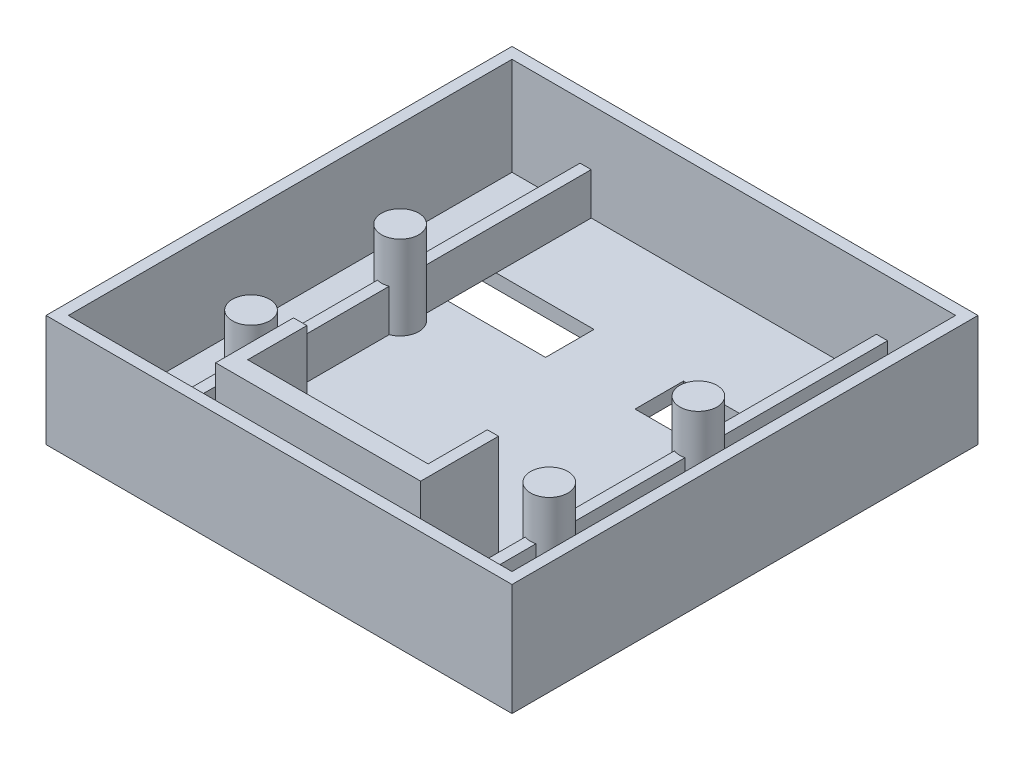
SolidWorks part; units mm, degrees
ref_plane "Alzado" through (0, 0, 0) normal (0, 0, 1) x (1, 0, 0)
ref_plane "Planta" through (0, 0, 0) normal (0, 1, 0) x (1, 0, 0)
ref_plane "Vista lateral" through (0, 0, 0) normal (1, 0, 0) x (0, 0, -1)
sketch "Croquis1" plane through (0, 0, 0) normal (0, 1, 0) x (1, 0, 0)
  line L1 (0, 0) -> (100, 0)
  line L2 (0, 0) -> (0, 100)
  line L3 (0, 100) -> (100, 100)
  line L4 (100, 0) -> (100, 100)
extrude "PlacaBase" add sketch "Croquis1" along normal blind 3
ref_plane "PL_SobreBase" through (0, 3, 0) normal (0, 1, 0) x (1, 0, 0)
sketch "Croquis2" plane through (0, 3, 0) normal (0, 1, 0) x (1, 0, 0)
  line L1 (0, 0) -> (100, 0)
  line L2 (0, 0) -> (0, 100)
  line L3 (0, 100) -> (100, 100)
  line L4 (100, 0) -> (100, 100)
  line L5 (2.4, 2.4) -> (97.6, 2.4)
  line L6 (2.4, 2.4) -> (2.4, 97.6)
  line L7 (2.4, 97.6) -> (97.6, 97.6)
  line L8 (97.6, 2.4) -> (97.6, 97.6)
extrude "Paredes" add sketch "Croquis2" along normal blind 21
sketch "RecortesRueda" plane through (0, 0, 0) normal (0, 1, 0) x (1, 0, 0)
  line L0 (0, 100) -> (0, 0) construction
  line L1 (0, 53) -> (14, 53)
  line L2 (0, 53) -> (0, 91)
  line L3 (0, 91) -> (14, 91)
  line L4 (14, 53) -> (14, 91)
  line L5 (100, 0) -> (100, 100) construction
  line L6 (86, 53) -> (100, 53)
  line L7 (86, 53) -> (86, 91)
  line L8 (86, 91) -> (100, 91)
  line L9 (100, 53) -> (100, 91)
ref_plane "PL_Motores" through (0, 7.3, 0) normal (0, 1, 0) x (1, 0, 0)
sketch "Croquis4" plane through (0, 7.3, 0) normal (0, 1, 0) x (1, 0, 0)
  line L0 (14, 53) -> (14, 91) construction
  line L1 (14, 66.8) -> (40.4, 66.8)
  line L2 (14, 66.8) -> (14, 77.2)
  line L3 (14, 77.2) -> (40.4, 77.2)
  line L4 (40.4, 66.8) -> (40.4, 77.2)
  line L5 (86, 53) -> (86, 91) construction
  line L6 (59.6, 66.8) -> (86, 66.8)
  line L7 (59.6, 66.8) -> (59.6, 77.2)
  line L8 (59.6, 77.2) -> (86, 77.2)
  line L9 (86, 66.8) -> (86, 77.2)
extrude "AlojamientosMotor" cut sketch "Croquis4" against normal blind 12.4
ref_plane "PL_Superior" through (0, 24, 0) normal (0, 1, 0) x (1, 0, 0)
sketch "BolsilloBateria" plane through (0, 24, 0) normal (0, 1, 0) x (1, 0, 0)
  line L1 (22, 26) -> (78, 26)
  line L2 (22, 26) -> (22, 57)
  line L3 (22, 57) -> (78, 57)
  line L4 (78, 26) -> (78, 57)
sketch "Croquis6" plane through (0, 3, 0) normal (0, 1, 0) x (1, 0, 0)
  line L0 (2.4, 2.4) -> (97.6, 2.4) construction
  line L1 (17, 2.4) -> (19.4, 2.4)
  line L2 (17, 2.4) -> (17, 97.6)
  line L3 (17, 97.6) -> (19.4, 97.6)
  line L4 (19.4, 2.4) -> (19.4, 97.6)
  line L5 (97.6, 97.6) -> (2.4, 97.6) construction
  line L7 (80.6, 2.4) -> (83, 2.4)
  line L8 (80.6, 2.4) -> (80.6, 97.6)
  line L9 (80.6, 97.6) -> (83, 97.6)
  line L10 (83, 2.4) -> (83, 97.6)
extrude "NerviosRigidez" add sketch "Croquis6" along normal blind 9
sketch "Croquis7" plane through (0, 3, 0) normal (0, 1, 0) x (1, 0, 0)
  line L0 (97.6, 2.4) -> (97.6, 97.6) construction
  line L1 (2.4, 2.4) -> (97.6, 2.4)
  line L2 (2.4, 2.4) -> (2.4, 8.4)
  line L3 (2.4, 8.4) -> (97.6, 8.4)
  line L4 (97.6, 2.4) -> (97.6, 8.4)
extrude "BloqueCuna" add sketch "Croquis7" along normal blind 10
sketch "Croquis8" plane through (0, 3, 0) normal (0, 1, 0) x (1, 0, 0)
  line L0 (80.6, 8.4) -> (19.4, 8.4) construction
  line L1 (28, 8.4) -> (72, 8.4)
  line L2 (28, 8.4) -> (28, 12.4)
  line L3 (28, 12.4) -> (72, 12.4)
  line L4 (72, 8.4) -> (72, 12.4)
extrude "TorreSensores" add sketch "Croquis8" along normal blind 22
sketch "VentanasSensoresLinea" plane through (0, 0, 0) normal (0, 1, 0) x (1, 0, 0)
  circle A0 centre (26, 24) radius 5
  circle A1 centre (74, 24) radius 5
  circle A2 centre (26, 94) radius 5
  circle A3 centre (74, 94) radius 5
sketch "AnclajesInsertos" plane through (0, 0, 0) normal (0, 1, 0) x (1, 0, 0)
  circle A0 centre (40, 62) radius 2.1
  circle A1 centre (60, 62) radius 2.1
  circle A2 centre (40, 82) radius 2.1
  circle A3 centre (60, 82) radius 2.1
  circle A4 centre (12, 16) radius 2.1
  circle A5 centre (88, 16) radius 2.1
sketch "Croquis11" plane through (0, 3, 0) normal (0, 1, 0) x (1, 0, 0)
  line L0 (72, 12.4) -> (28, 12.4) construction
  line L1 (28, 12.4) -> (30.8757, 12.4)
  line L2 (28, 12.4) -> (28, 25.1081)
  line L3 (28, 25.1081) -> (30.8757, 25.1081)
  line L4 (30.8757, 12.4) -> (30.8757, 25.1081)
  line L5 (69.6, 12.4) -> (72, 12.4)
  line L6 (69.6, 12.4) -> (69.6, 25.1081)
  line L7 (69.6, 25.1081) -> (72, 25.1081)
  line L8 (72, 12.4) -> (72, 25.1081)
  circle A0 centre (26, 24) radius 5 construction
extrude "NerviosTorre" add sketch "Croquis11" along normal blind 22
sketch "Croquis12" plane through (0, 3, 0) normal (0, 1, 0) x (1, 0, 0)
  circle A0 centre (18, 26) radius 4
  circle A1 centre (82, 26) radius 4
  circle A2 centre (18, 58) radius 4
  circle A3 centre (82, 58) radius 4
extrude "PostesPlaca" add sketch "Croquis12" along normal blind 18
ref_plane "PL_Postes" through (0, 21, 0) normal (0, 1, 0) x (1, 0, 0)
sketch "PozosInsertoM2" plane through (0, 21, 0) normal (0, 1, 0) x (1, 0, 0)
  circle A0 centre (18, 26) radius 1.6
  circle A1 centre (82, 26) radius 1.6
  circle A2 centre (18, 58) radius 1.6
  circle A3 centre (82, 58) radius 1.6
equation "\"ANCHO\" = 100"
equation "\"PROF\" = 100"
equation "\"ALT\" = 24"
equation "\"BASE_T\" = 3"
equation "\"PARED\" = 2.4"
equation "\"EJE_Y\" = 72"
equation "\"EJE_Z\" = 13.5"
equation "\"RUEDA_D\" = 35"
equation "\"RUEDA_W\" = 12"
equation "\"MOT_L\" = 26"
equation "\"AJUSTE\" = 0.4"
